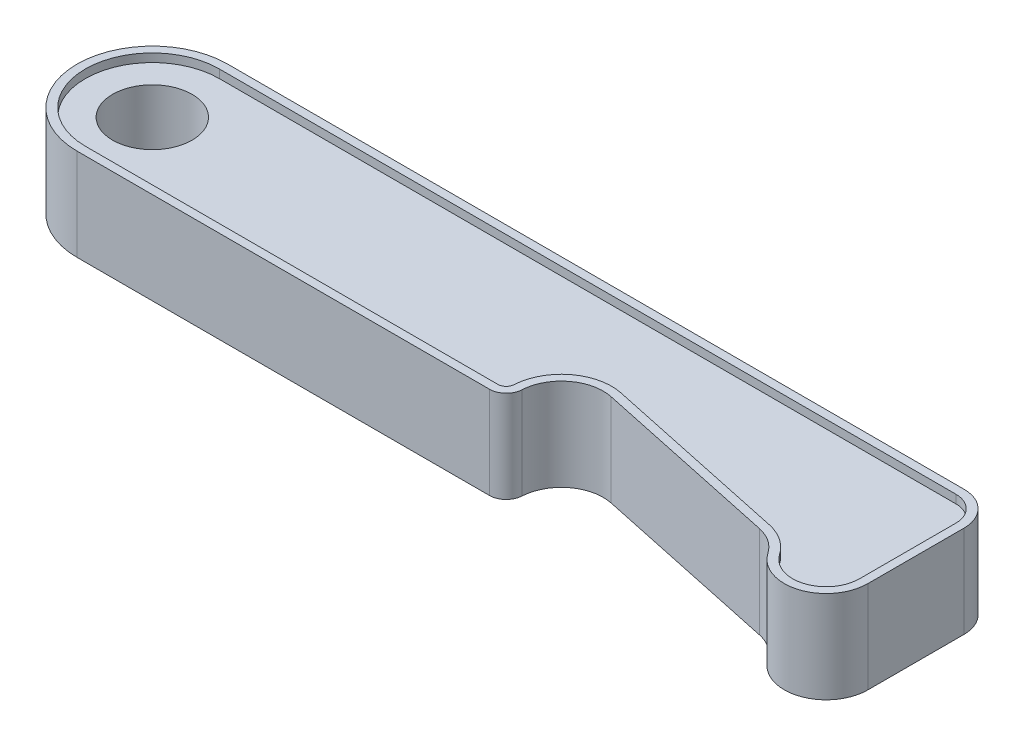
SolidWorks part; units mm, degrees
material "AISI 1020"
ref_plane "Front Plane" through (0, 0, 0) normal (0, 0, 1) x (1, 0, 0)
ref_plane "Top Plane" through (0, 0, 0) normal (0, 1, 0) x (1, 0, 0)
ref_plane "Right Plane" through (0, 0, 0) normal (1, 0, 0) x (0, 0, -1)
sketch "Sketch1" plane through (0, 0, 0) normal (0, 1, 0) x (1, 0, 0)
  line L0 (19.4913, 0.9889) -> (41.9913, -3.7936)
  line L2 (-37.817, -5.5057) -> (11.4629, -5.5057)
  line L4 (-37.817, 12.4943) -> (50.183, 12.4943)
  line L5 (54.183, -3.0057) -> (54.183, 8.4943)
  arc A0 (-37.817, 12.4943) -> (-37.817, -5.5057) centre (-37.817, 3.4943) ccw
  circle A1 centre (-37.817, 3.4943) radius 4.75
  arc A2 (54.183, 8.4943) -> (50.183, 12.4943) centre (50.183, 8.4943) ccw
  arc A3 (11.4629, -5.5057) -> (13.4597, -3.6189) centre (11.4629, -3.5057) ccw
  arc A5 (19.4913, 0.9889) -> (13.4597, -3.6189) centre (18.4517, -3.9018) ccw
  arc A8 (45.0674, -5.845) -> (41.9913, -3.7936) centre (40.9517, -8.6843) ccw
  arc A10 (45.0674, -5.845) -> (54.183, -3.0057) centre (49.183, -3.0057) ccw
  point P1 (0, 0)
  point P4 (-46.817, 3.4943)
  point P16 (54.183, -4.6955)
  point P23 (0, 0)
  point P24 (54.5612, -5.3225)
  dimension "D1" = 18
  dimension "D4" = 9.5
  dimension "D5" = 4
  dimension "D6" = 4
  dimension "D7" = 10
  dimension "D9" = 10
  dimension "D10" = 10
  dimension "D2" = 101
  dimension "D3" = 9
  dimension "D8" = 12
  dimension "D11" = 22.5
  dimension "D12" = 15.5
extrude "Boss-Extrude1" add sketch "Sketch1" along normal blind 11 contours A0 L2 A3 A5 L0 A8 A10 L5 A2 L4 | A1
sketch "Sketch2" plane through (0, 11, 0) normal (0, 1, 0) x (1, 0, 0)
  line L0 (50.183, 11.4943) -> (-37.817, 11.4943)
  line L1 (-37.817, -4.5057) -> (11.4629, -4.5057)
  line L2 (19.6992, 1.9671) -> (42.1992, -2.8154)
  line L3 (53.183, -3.0057) -> (53.183, 8.4943)
  line L4 (50.183, 12.4943) -> (-37.817, 12.4943)
  line L5 (-37.817, -5.5057) -> (11.4629, -5.5057)
  line L6 (19.4913, 0.9889) -> (41.9913, -3.7936)
  line L7 (54.183, -3.0057) -> (54.183, 8.4943)
  line L8 (50.183, 12.4943) -> (-37.817, 12.4943)
  line L9 (-37.817, -5.5057) -> (11.4629, -5.5057)
  line L10 (19.4913, 0.9889) -> (41.9913, -3.7936)
  line L11 (54.183, -3.0057) -> (54.183, 8.4943)
  arc A0 (-37.817, 11.4943) -> (-37.817, -4.5057) centre (-37.817, 3.4943) ccw
  arc A1 (11.4629, -4.5057) -> (12.4613, -3.5623) centre (11.4629, -3.5057) ccw
  arc A2 (19.6992, 1.9671) -> (12.4613, -3.5623) centre (18.4517, -3.9018) ccw
  arc A3 (45.8905, -5.2772) -> (42.1992, -2.8154) centre (40.9517, -8.6843) ccw
  arc A4 (45.8905, -5.2772) -> (53.183, -3.0057) centre (49.183, -3.0057) ccw
  arc A5 (53.183, 8.4943) -> (50.183, 11.4943) centre (50.183, 8.4943) ccw
  arc A6 (-37.817, 12.4943) -> (-37.817, -5.5057) centre (-37.817, 3.4943) ccw
  arc A7 (11.4629, -5.5057) -> (13.4597, -3.6189) centre (11.4629, -3.5057) ccw
  arc A8 (19.4913, 0.9889) -> (13.4597, -3.6189) centre (18.4517, -3.9018) ccw
  arc A9 (45.0674, -5.845) -> (41.9913, -3.7936) centre (40.9517, -8.6843) ccw
  arc A10 (45.0674, -5.845) -> (54.183, -3.0057) centre (49.183, -3.0057) ccw
  arc A11 (54.183, 8.4943) -> (50.183, 12.4943) centre (50.183, 8.4943) ccw
  arc A12 (-37.817, 12.4943) -> (-37.817, -5.5057) centre (-37.817, 3.4943) ccw
  arc A13 (11.4629, -5.5057) -> (13.4597, -3.6189) centre (11.4629, -3.5057) ccw
  arc A14 (19.4913, 0.9889) -> (13.4597, -3.6189) centre (18.4517, -3.9018) ccw
  arc A15 (45.0674, -5.845) -> (41.9913, -3.7936) centre (40.9517, -8.6843) ccw
  arc A16 (45.0674, -5.845) -> (54.183, -3.0057) centre (49.183, -3.0057) ccw
  arc A17 (54.183, 8.4943) -> (50.183, 12.4943) centre (50.183, 8.4943) ccw
  circle M22 centre (-37.817, 3.4943) radius 4.75
  dimension "D2" = 1
extrude "Cut-Extrude1" cut sketch "Sketch2" against normal blind 1 contours L3 A5 L0 A0 L1 A2 L2 A3 A4 M22 | L8 A12 L9 A13 A14 L10 A15 A16 L11 A17
sketch "Sketch3" plane through (0, 0, 0) normal (0, -1, 0) x (1, 0, 0)
  line L0 (11.4629, 4.5057) -> (-37.817, 4.5057)
  line L1 (-37.817, -11.4943) -> (50.183, -11.4943)
  line L2 (53.183, -8.4943) -> (53.183, 3.0057)
  line L3 (42.1992, 2.8154) -> (19.6992, -1.9671)
  line L4 (-37.817, -12.4943) -> (50.183, -12.4943)
  line L5 (54.183, -8.4943) -> (54.183, 3.0057)
  line L6 (41.9913, 3.7936) -> (19.4913, -0.9889)
  line L7 (11.4629, 5.5057) -> (-37.817, 5.5057)
  line L8 (-37.817, -12.4943) -> (50.183, -12.4943)
  line L9 (54.183, -8.4943) -> (54.183, 3.0057)
  line L10 (41.9913, 3.7936) -> (19.4913, -0.9889)
  line L11 (11.4629, 5.5057) -> (-37.817, 5.5057)
  arc A0 (-37.817, 4.5057) -> (-37.817, -11.4943) centre (-37.817, -3.4943) ccw
  arc A1 (50.183, -11.4943) -> (53.183, -8.4943) centre (50.183, -8.4943) ccw
  arc A2 (53.183, 3.0057) -> (45.8905, 5.2772) centre (49.183, 3.0057) ccw
  arc A3 (42.1992, 2.8154) -> (45.8905, 5.2772) centre (40.9517, 8.6843) ccw
  arc A4 (12.4613, 3.5623) -> (19.6992, -1.9671) centre (18.4517, 3.9018) ccw
  arc A5 (12.4613, 3.5623) -> (11.4629, 4.5057) centre (11.4629, 3.5057) ccw
  arc A6 (50.183, -12.4943) -> (54.183, -8.4943) centre (50.183, -8.4943) ccw
  arc A7 (54.183, 3.0057) -> (45.0674, 5.845) centre (49.183, 3.0057) ccw
  arc A8 (41.9913, 3.7936) -> (45.0674, 5.845) centre (40.9517, 8.6843) ccw
  arc A9 (13.4597, 3.6189) -> (19.4913, -0.9889) centre (18.4517, 3.9018) ccw
  arc A10 (13.4597, 3.6189) -> (11.4629, 5.5057) centre (11.4629, 3.5057) ccw
  arc A11 (-37.817, 5.5057) -> (-37.817, -12.4943) centre (-37.817, -3.4943) ccw
  arc A12 (50.183, -12.4943) -> (54.183, -8.4943) centre (50.183, -8.4943) ccw
  arc A13 (54.183, 3.0057) -> (45.0674, 5.845) centre (49.183, 3.0057) ccw
  arc A14 (41.9913, 3.7936) -> (45.0674, 5.845) centre (40.9517, 8.6843) ccw
  arc A15 (13.4597, 3.6189) -> (19.4913, -0.9889) centre (18.4517, 3.9018) ccw
  arc A16 (13.4597, 3.6189) -> (11.4629, 5.5057) centre (11.4629, 3.5057) ccw
  arc A17 (-37.817, 5.5057) -> (-37.817, -12.4943) centre (-37.817, -3.4943) ccw
  circle M22 centre (-37.817, -3.4943) radius 4.75
  dimension "D2" = 1
extrude "Cut-Extrude2" cut sketch "Sketch3" against normal blind 1 contours A4 L0 A0 L1 A1 L2 A2 A3 L3 M22 | L8 A12 L9 A13 A14 L10 A15 A16 L11 A17
equation "\"A\" = 101"
equation "\"B\" = 11"
equation "\"C\"= 1"
equation "\"D2@Sketch1\"=\"A\""
equation "\"D1@Boss-Extrude1\"=\"B\""
equation "\"D2@Sketch2\"=\"C\""
equation "\"D1@Cut-Extrude1\"=\"C\""
equation "\"D2@Sketch3\"=\"C\""
equation "\"D1@Cut-Extrude2\"=\"C\""
